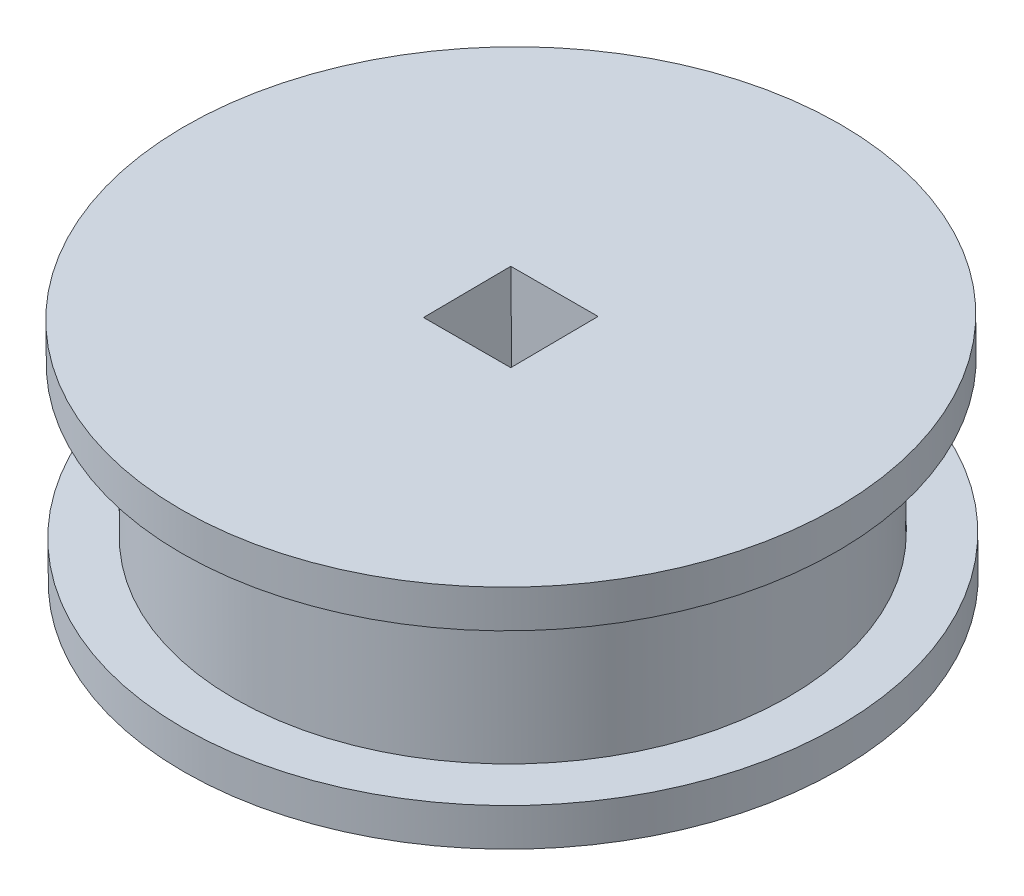
SolidWorks part; units mm, degrees
ref_plane "Front Plane" through (0, 0, 0) normal (0, 0, 1) x (1, 0, 0)
ref_plane "Top Plane" through (0, 0, 0) normal (0, 1, 0) x (1, 0, 0)
ref_plane "Right Plane" through (0, 0, 0) normal (1, 0, 0) x (0, 0, -1)
sketch "Sketch2" plane through (-0.006, 2.8431, 0.0241) normal (-0.0021, 1, 0.0085) x (1, 0.0021, 0)
  circle A0 centre (0, 1.5999) radius 11
  dimension "D1" = 22
extrude "Boss-Extrude1" add sketch "Sketch2" along normal blind 6
sketch "Sketch3" plane through (-0.0188, 8.8429, 0.0748) normal (-0.0021, 1, 0.0085) x (1, 0.0021, 0)
  line L0 (0, -0.1251) -> (0, 1.5999) construction
  line L1 (-1.725, -0.1251) -> (1.725, -0.1251)
  line L2 (-1.725, -0.1251) -> (-1.725, 3.3249)
  line L3 (-1.725, 3.3249) -> (1.725, 3.3249)
  line L4 (1.725, 3.3249) -> (1.725, -0.1251)
  circle A1 centre (0, 1.5999) radius 2.0642 construction
  point P6 (0, -0.1251)
  dimension "D1" = 3.45
  dimension "D2" = 1.725
extrude "Cut-Extrude1" cut sketch "Sketch3" against normal through all
ref_plane "Plane1" through (-0.0124, 5.843, 0.0495) normal (0.0021, -1, -0.0085) x (-1, -0.0021, 0)
sketch "Sketch4" plane through (-0.0188, 8.8429, 0.0748) normal (-0.0021, 1, 0.0085) x (1, 0.0021, 0)
  circle A0 centre (0, 1.5999) radius 13
  dimension "D1" = 26
extrude "Boss-Extrude2" add sketch "Sketch4" along normal blind 1.5
mirror "Mirror1" about plane through (-0.0124, 5.843, 0.0495) normal (0.0021, -1, -0.0085) of "Boss-Extrude2"
sketch "Sketch5" plane through (-0.022, 10.3428, 0.0875) normal (-0.0021, 1, 0.0085) x (1, 0.0021, 0)
  line L4 (-1.725, -0.1251) -> (1.725, -0.1251)
  line L5 (1.725, -0.1251) -> (1.725, 3.3249)
  line L6 (1.725, 3.3249) -> (-1.725, 3.3249)
  line L7 (-1.725, 3.3249) -> (-1.725, -0.1251)
  line L8 (-1.725, -0.1251) -> (1.725, -0.1251)
  line L9 (1.725, -0.1251) -> (1.725, 3.3249)
  line L10 (1.725, 3.3249) -> (-1.725, 3.3249)
  line L11 (-1.725, 3.3249) -> (-1.725, -0.1251)
  dimension "D1" = 0
extrude "Cut-Extrude2" cut sketch "Sketch5" against normal through all
